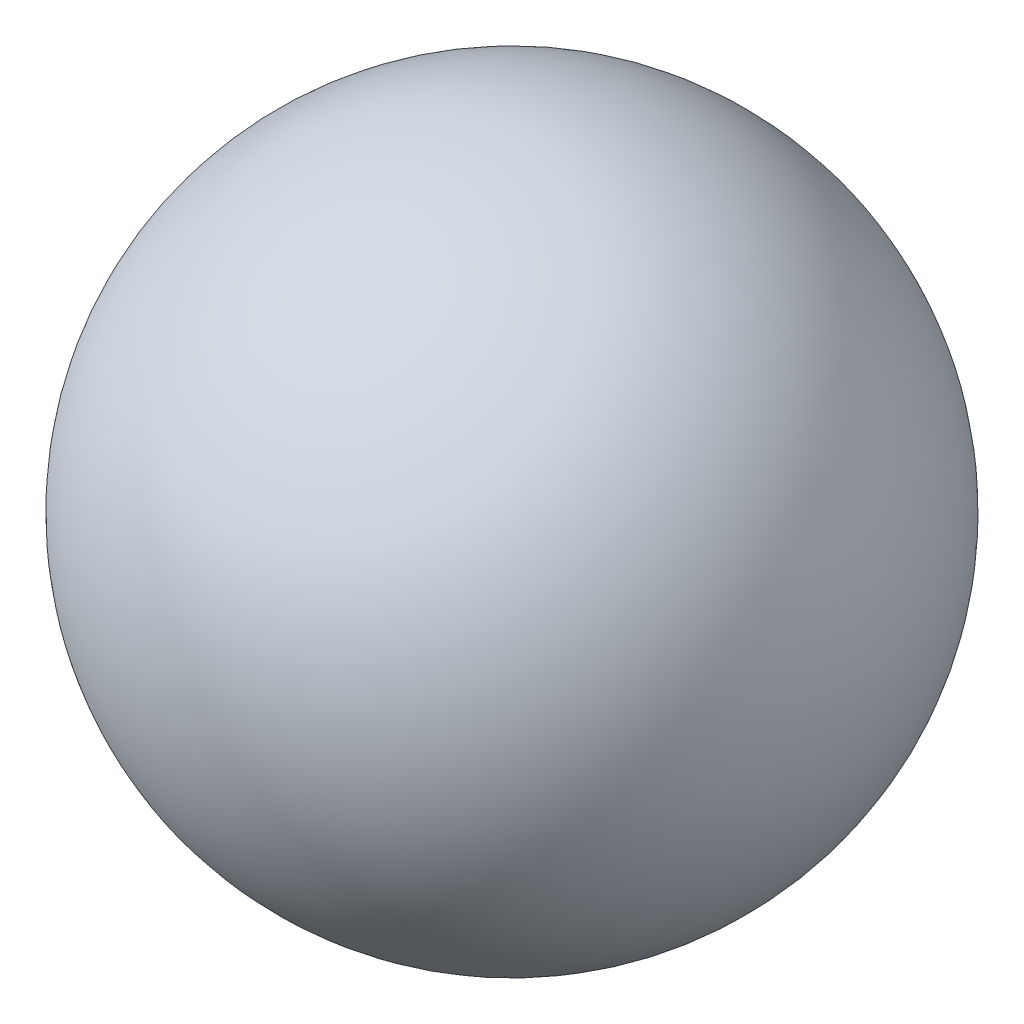
SolidWorks part; units mm, degrees
ref_plane "Front Plane" through (0, 0, 0) normal (0, 0, 1) x (1, 0, 0)
ref_plane "Top Plane" through (0, 0, 0) normal (0, 1, 0) x (1, 0, 0)
ref_plane "Right Plane" through (0, 0, 0) normal (1, 0, 0) x (0, 0, -1)
sketch "Sketch1" plane through (0, 0, 0) normal (0, 1, 0) x (1, 0, 0)
  line L0 (0, 0) -> (0, -76.2)
  arc A0 (0, 0) -> (0, -76.2) centre (0, -38.1) ccw
  dimension "D1" = 76.2
revolve "Revolve4" add sketch "Sketch1" angle 360 about L0
